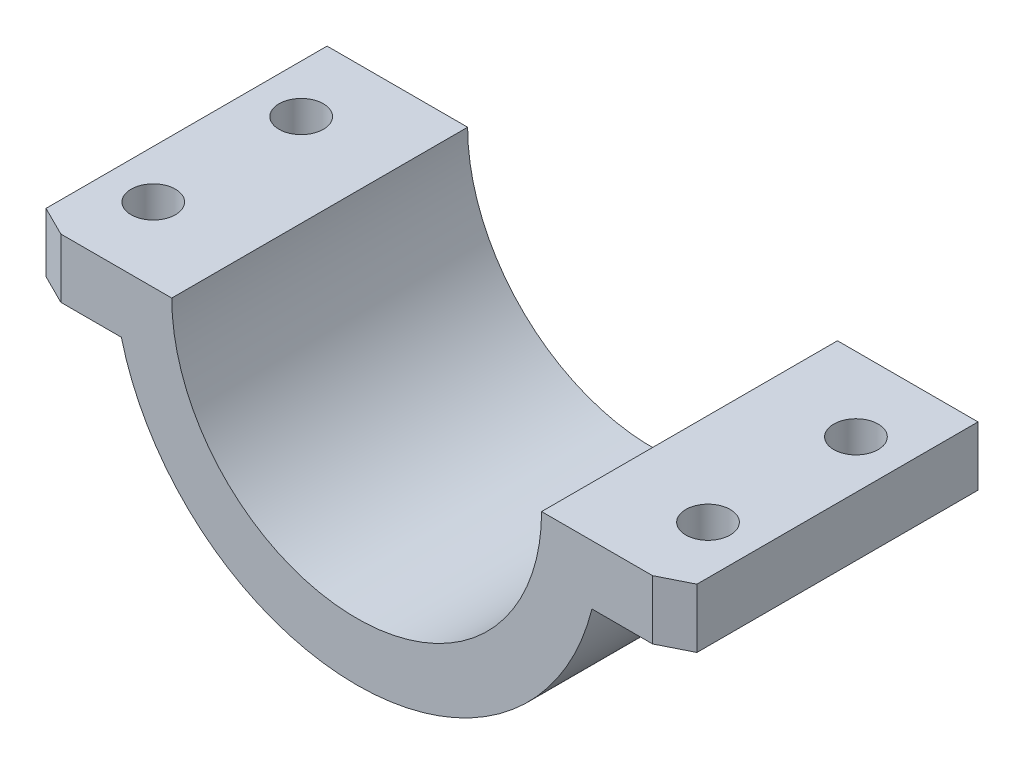
SolidWorks part; units mm, degrees
material "PVC 0.007 Plasticizado"
ref_plane "Plano frontal" through (0, 0, 0) normal (0, 0, 1) x (1, 0, 0)
ref_plane "Plano superior" through (0, 0, 0) normal (0, 1, 0) x (1, 0, 0)
ref_plane "Plano direito" through (0, 0, 0) normal (1, 0, 0) x (0, 0, -1)
sketch "Esboço1" plane through (0, 0, 0) normal (0, 0, 1) x (1, 0, 0)
  line L0 (-54.9481, 11.8949) -> (-45.4481, 11.8949)
  line L1 (-10.9481, 11.8949) -> (-10.9481, 7.8949)
  line L2 (-10.9481, 7.8949) -> (-17.0434, 7.8949)
  line L3 (-54.9481, 7.8949) -> (-54.9481, 11.8949)
  line L4 (-20.4481, 11.8949) -> (-10.9481, 11.8949)
  line L5 (-48.8528, 7.8949) -> (-54.9481, 7.8949)
  arc A0 (-45.4481, 11.8949) -> (-20.4481, 11.8949) centre (-32.9481, 11.8949) ccw
  arc A1 (-48.8528, 7.8949) -> (-17.0434, 7.8949) centre (-32.9481, 11.8949) ccw
extrude "Ressalto-extrusão1" add sketch "Esboço1" along normal blind 20
sketch "Esboço2" plane through (0, 11.8949, 0) normal (0, 1, 0) x (1, 0, 0)
  circle A0 centre (-51.6981, -5) radius 1.5
  circle A1 centre (-51.6981, -15) radius 1.5
  circle A2 centre (-14.1981, -5) radius 1.5
  circle A3 centre (-14.1981, -15) radius 1.5
extrude "Corte-extrusão1" cut sketch "Esboço2" against normal through all
sketch "Esboço3" plane through (0, 11.8949, 0) normal (0, 1, 0) x (1, 0, 0)
  line L0 (-10.9481, -21.14) -> (-8.7754, -20.4809)
  line L1 (-8.7754, -20.4809) -> (-9.1775, -19.8515)
  line L2 (-9.1775, -19.8515) -> (-10.9481, -19)
  line L17 (-54.9481, -19) -> (-52.9481, -20)
  line L18 (-52.9481, -22.6284) -> (-56.7623, -22.6284)
  line L19 (-56.7623, -22.6284) -> (-56.7623, -19)
  line L20 (-56.7623, -19) -> (-54.9481, -19)
  line L21 (-52.9481, -22.6284) -> (-52.9481, -20)
  line L22 (-12.9481, -20) -> (-10.9481, -19)
  line L23 (-12.9481, -20) -> (-13.2388, -21.14)
  line L24 (-13.2388, -21.14) -> (-10.9481, -21.14)
extrude "Corte-extrusão2" cut sketch "Esboço3" against normal through all
